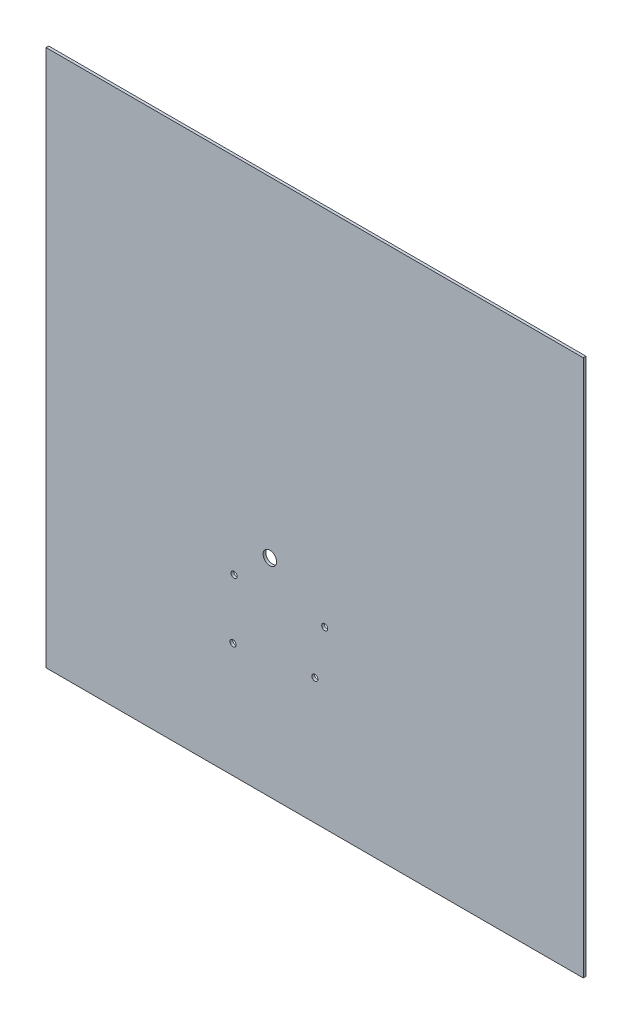
SolidWorks part; units mm, degrees
ref_plane "前基準面" through (0, 0, 0) normal (0, 0, 1) x (1, 0, 0)
ref_plane "上基準面" through (0, 0, 0) normal (0, 1, 0) x (1, 0, 0)
ref_plane "右基準面" through (0, 0, 0) normal (1, 0, 0) x (0, 0, -1)
sketch "草圖1" plane through (0, 0, 0) normal (0, 0, 1) x (1, 0, 0)
  line L1 (-162.1895, 422.8649) -> (237.8105, 422.8649)
  line L2 (-162.1895, 422.8649) -> (-162.1895, 22.8649)
  line L3 (-162.1895, 22.8649) -> (237.8105, 22.8649)
  line L4 (237.8105, 422.8649) -> (237.8105, 22.8649)
  circle A0 centre (-22.1895, 152.8649) radius 2.25
  circle A1 centre (45.3105, 152.8649) radius 2.25
  circle A2 centre (37.9743, 116.5994) radius 2.25
  circle A3 centre (-22.9729, 108.3718) radius 2.25
  circle A4 centre (4.4475, 177.082) radius 5
  dimension "D3" = 270
  dimension "D4" = 67.5
  dimension "D5" = 260
  dimension "D6" = 37
  dimension "D7" = 44.5
  dimension "D8" = 81.5
  dimension "D9" = 4.5
  dimension "D10" = 61.5
  dimension "D11" = 4.5
  dimension "D12" = 4.5
  dimension "D13" = 4.5
  dimension "D14" = 47.5
  dimension "D15" = 36
  dimension "D16" = 10
  dimension "D1" = 400
  dimension "D2" = 400
extrude "填料-伸長1" add sketch "草圖1" along normal blind 2
